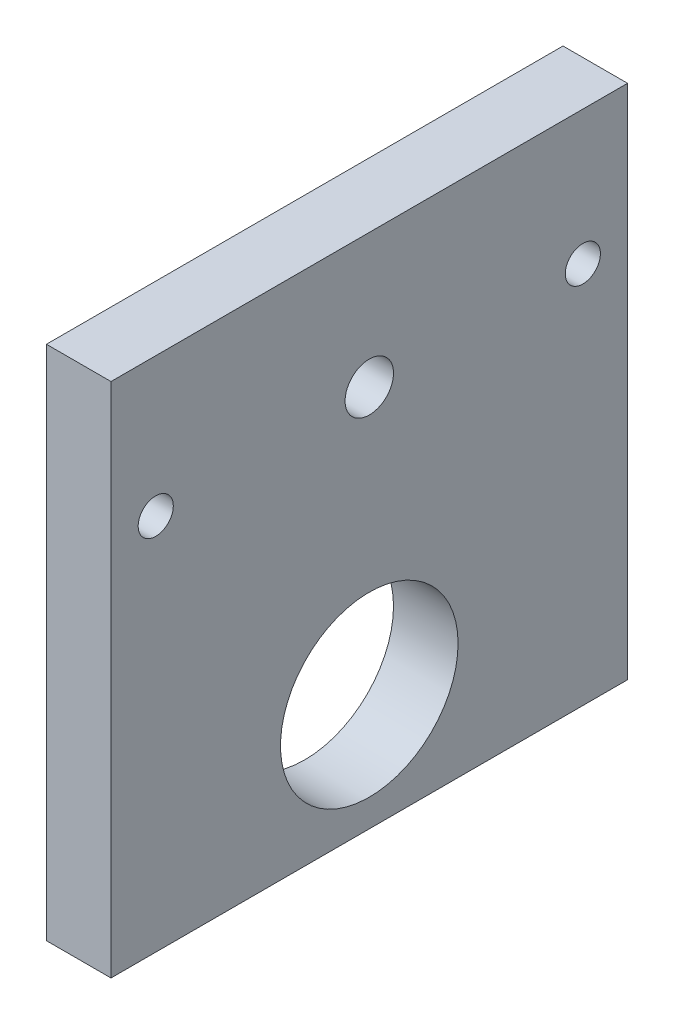
SolidWorks part; units mm, degrees
ref_plane "Front Plane" through (0, 0, 0) normal (0, 0, 1) x (1, 0, 0)
ref_plane "Top Plane" through (0, 0, 0) normal (0, 1, 0) x (1, 0, 0)
ref_plane "Right Plane" through (0, 0, 0) normal (1, 0, 0) x (0, 0, -1)
sketch "Sketch1" plane through (0, 0, 0) normal (1, 0, 0) x (0, 0, -1)
  line L1 (-25.4, -25.4) -> (25.4, -25.4)
  line L2 (-25.4, -25.4) -> (-25.4, 25.4)
  line L3 (-25.4, 25.4) -> (25.4, 25.4)
  line L4 (25.4, -25.4) -> (25.4, 25.4)
  line L5 (-25.4, -25.4) -> (25.4, 25.4) construction
  line L6 (-25.4, 25.4) -> (25.4, -25.4) construction
  point P0 (0, 0)
  dimension "D1" = 50.8
  dimension "D2" = 50.8
extrude "Boss-Extrude1" add sketch "Sketch1" along normal blind 6.35
hole_wizard "11/16 (0.6875) Diameter Hole1" positions "Sketch9" profile "Sketch8" hole size "11/16" standard "ANSI Inch"
sketch "Sketch9" plane through (6.35, 0, 0) normal (1, 0, 0) x (0, 0, -1)
  line L0 (-25.4, -25.4) -> (25.4, -25.4) construction
  point P0 (0, -13.97)
  dimension "D1" = 11.43
sketch "Sketch8" plane through (6.35, -13.97, 0) normal (0, 1, 0) x (0, 0, -1)
  line L0 (0, 0) -> (0, 75.3503)
  line L1 (0, 75.3503) -> (8.7312, 70.104)
  line L2 (8.7312, 70.104) -> (8.7312, 0)
  line L5 (8.7312, 0) -> (0, 0)
  line L10 (0, 75.3503) -> (-8.7313, 70.104) construction
  line L11 (0, -6.35) -> (0, 107.95) construction
  dimension "Hole Dia." = 17.4625
  dimension "Hole Depth" = 70.104
  dimension "Drill Angle" = 118
hole_wizard "3/16 (0.1875) Diameter Hole1" positions "Sketch3" profile "Sketch2" hole size "3/16" standard "ANSI Inch"
sketch "Sketch3" plane through (6.35, 0, 0) normal (1, 0, 0) x (0, 0, -1)
  circle A0 centre (0, -13.97) radius 8.7312 construction
  point P0 (0, 12.2301)
  dimension "D1" = 26.2001
  dimension "D2" = 0
sketch "Sketch2" plane through (6.35, 12.2301, 0) normal (0, 1, 0) x (0, 0, -1)
  line L0 (0, 0) -> (0, 71.5348)
  line L1 (0, 71.5348) -> (2.3812, 70.104)
  line L2 (2.3812, 70.104) -> (2.3812, 0)
  line L5 (2.3812, 0) -> (0, 0)
  line L10 (0, 71.5348) -> (-2.3813, 70.104) construction
  line L11 (0, -6.35) -> (0, 107.95) construction
  dimension "Hole Dia." = 4.7625
  dimension "Hole Depth" = 70.104
  dimension "Drill Angle" = 118
hole_wizard "#29 (0.136) Diameter Hole1" positions "Sketch5" profile "Sketch4" hole size "#29" standard "ANSI Inch"
sketch "Sketch5" plane through (6.35, 0, 0) normal (1, 0, 0) x (0, 0, -1)
  circle A0 centre (0, 12.2301) radius 2.3812 construction
  point P0 (21, 12.2301)
  point P2 (-21, 11.7415)
  dimension "D1" = 0.4886
  dimension "D2" = 0
  dimension "D3" = 21
  dimension "D4" = 42
sketch "Sketch4" plane through (6.35, 12.2301, -21) normal (0, 1, 0) x (0, 0, -1)
  line L0 (0, 0) -> (0, 71.1418)
  line L1 (0, 71.1418) -> (1.7272, 70.104)
  line L2 (1.7272, 70.104) -> (1.7272, 0)
  line L5 (1.7272, 0) -> (0, 0)
  line L10 (0, 71.1418) -> (-1.7272, 70.104) construction
  line L11 (0, -6.35) -> (0, 107.95) construction
  dimension "Hole Dia." = 3.4544
  dimension "Hole Depth" = 70.104
  dimension "Drill Angle" = 118
